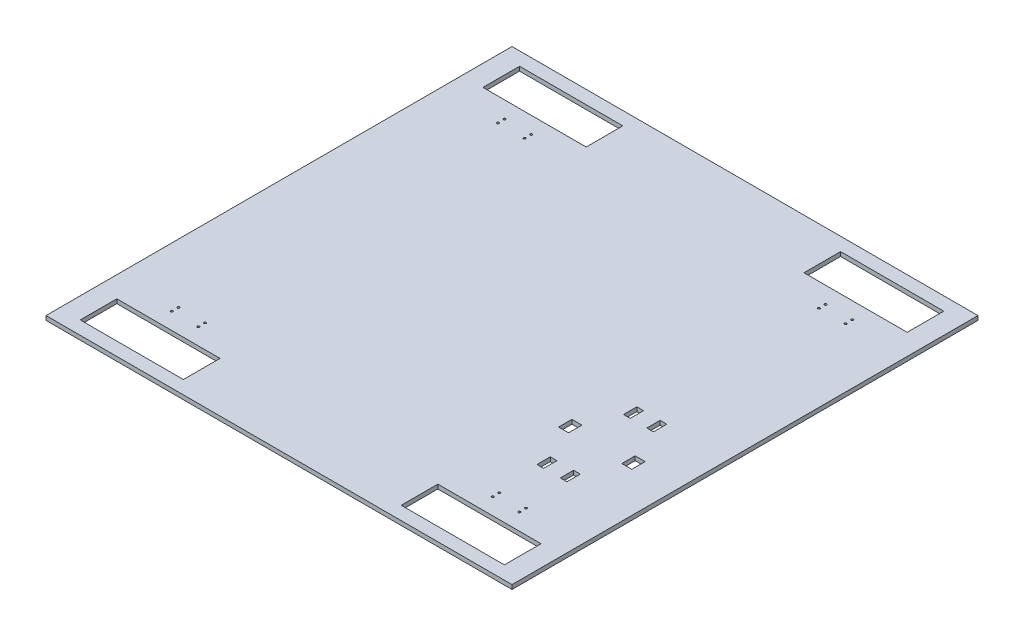
SolidWorks part; units mm, degrees
ref_plane "Front Plane" through (0, 0, 0) normal (0, 0, 1) x (1, 0, 0)
ref_plane "Top Plane" through (0, 0, 0) normal (0, 1, 0) x (1, 0, 0)
ref_plane "Right Plane" through (0, 0, 0) normal (1, 0, 0) x (0, 0, -1)
sketch "Sketch1" plane through (0, 0, 0) normal (0, 1, 0) x (1, 0, 0)
  line L1 (0, 0) -> (700, 0)
  line L2 (0, 0) -> (0, 700)
  line L3 (0, 700) -> (700, 700)
  line L4 (700, 0) -> (700, 700)
  dimension "D1" = 700
  dimension "D2" = 700
extrude "Boss-Extrude1" add sketch "Sketch1" along normal blind 6.35
sketch "Sketch2" plane through (0, 6.35, 0) normal (0, 1, 0) x (1, 0, 0)
  line L0 (700, 0) -> (700, 700) construction
  line L1 (611.1, 100) -> (571.1, 100)
  line L2 (611.1, 100) -> (611.1, 110)
  line L3 (611.1, 110) -> (571.1, 110)
  line L4 (571.1, 100) -> (571.1, 110)
  line L5 (611.1, 100) -> (571.1, 110) construction
  line L6 (611.1, 110) -> (571.1, 100) construction
  line L7 (0, 0) -> (700, 0) construction
  line L9 (513.6, 75) -> (668.6, 75)
  line L10 (513.6, 75) -> (513.6, 20)
  line L11 (513.6, 20) -> (668.6, 20)
  line L12 (668.6, 75) -> (668.6, 20)
  line L13 (513.6, 75) -> (668.6, 20) construction
  line L14 (513.6, 20) -> (668.6, 75) construction
  circle A0 centre (611.1, 100) radius 1.65
  circle A1 centre (611.1, 110) radius 1.65
  circle A2 centre (571.1, 110) radius 1.65
  circle A3 centre (571.1, 100) radius 1.65
  point P4 (591.1, 105)
  point P17 (591.1, 47.5)
  point P18 (591.1, 75)
  point P19 (591.1, 100)
  dimension "D3" = 3.3
  dimension "D1" = 40
  dimension "D2" = 10
  dimension "D4" = 88.9
  dimension "D5" = 100
  dimension "D6" = 25
  dimension "D7" = 55
  dimension "D8" = 155
extrude "Cut-Extrude2" cut sketch "Sketch2" against normal blind 10 contours L3 A2 L4 | L4 A2 L3 | L4 A3 L1 | L1 A3 L4 | L2 A1 L3 | L3 A1 L2 | L1 A0 L2 | L2 A0 L1 | L12 L9 L10 L11
ref_plane "Plane1" through (350, 0, 0) normal (1, 0, 0) x (0, 0, -1)
ref_plane "Plane2" through (0, 0, -350) normal (0, 0, 1) x (1, 0, 0)
mirror "Mirror1" about plane through (350, 0, 0) normal (1, 0, 0) of "Cut-Extrude2" second plane through (0, 0, -350) second plane normal (0, 0, 1)
sketch "Sketch3" plane through (0, 6.35, 0) normal (0, 1, 0) x (1, 0, 0)
  line L0 (700, 0) -> (700, 700) construction
  line L9 (562.5, 325) -> (572.5, 325)
  line L10 (562.5, 325) -> (562.5, 305)
  line L11 (562.5, 305) -> (572.5, 305)
  line L12 (572.5, 325) -> (572.5, 305)
  line L13 (597.5, 325) -> (607.5, 325)
  line L14 (597.5, 325) -> (597.5, 305)
  line L15 (597.5, 305) -> (607.5, 305)
  line L16 (607.5, 325) -> (607.5, 305)
  line L17 (530, 260) -> (545, 260)
  line L18 (530, 260) -> (530, 240)
  line L19 (530, 240) -> (545, 240)
  line L20 (545, 260) -> (545, 240)
  line L21 (625, 260) -> (640, 260)
  line L22 (625, 260) -> (625, 240)
  line L23 (625, 240) -> (640, 240)
  line L24 (640, 260) -> (640, 240)
  line L25 (562.5, 195) -> (572.5, 195)
  line L26 (562.5, 195) -> (562.5, 175)
  line L27 (562.5, 175) -> (572.5, 175)
  line L28 (572.5, 195) -> (572.5, 175)
  line L29 (597.5, 195) -> (607.5, 195)
  line L30 (597.5, 195) -> (597.5, 175)
  line L31 (597.5, 175) -> (607.5, 175)
  line L32 (607.5, 195) -> (607.5, 175)
  line L41 (0, 0) -> (700, 0) construction
  dimension "D3" = 10
  dimension "D4" = 10
  dimension "D5" = 10
  dimension "D6" = 10
  dimension "D12" = 20
  dimension "D13" = 20
  dimension "D14" = 20
  dimension "D16" = 20
  dimension "D18" = 80
  dimension "D19" = 15
  dimension "D20" = 15
  dimension "D21" = 20
  dimension "D22" = 20
  dimension "D23" = 60
  dimension "D24" = 240
  dimension "D26" = 45
  dimension "D27" = 110
extrude "Cut-Extrude3" cut sketch "Sketch3" against normal through all
